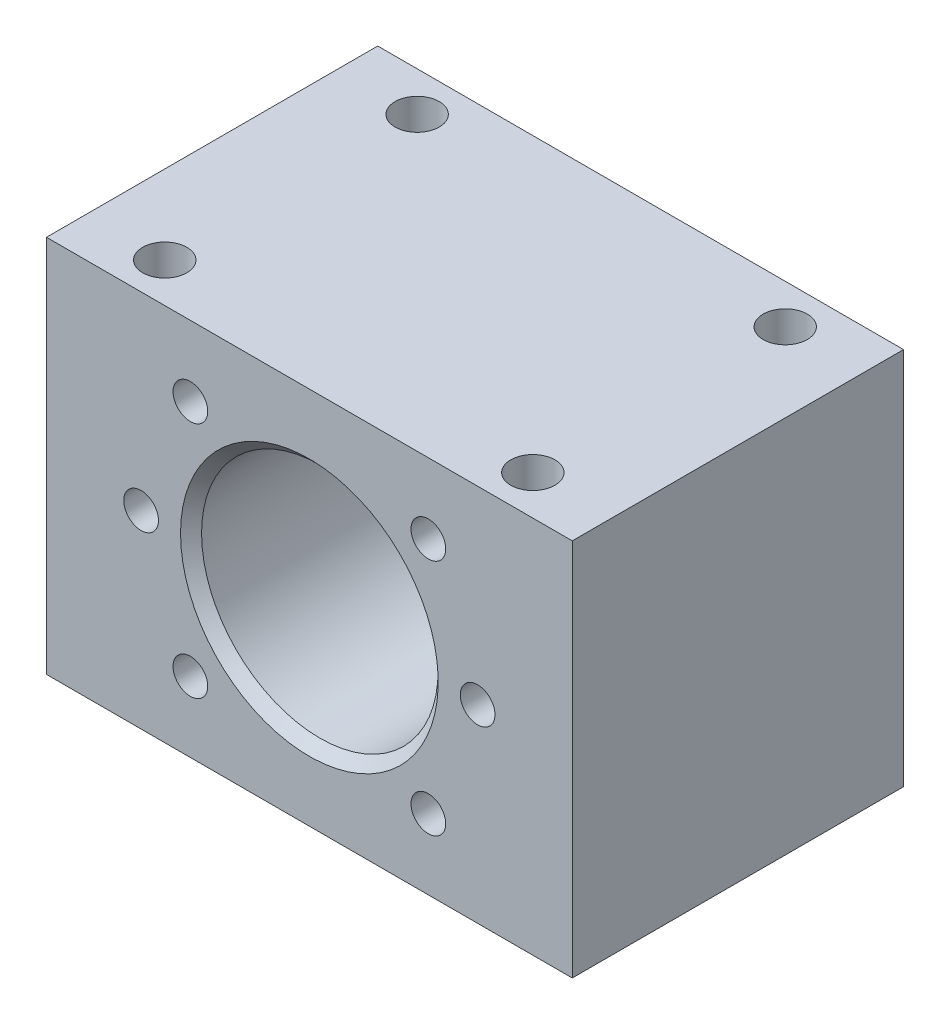
SolidWorks part; units mm, degrees
material "Alliage 1060"
ref_plane "Plan de face" through (0, 0, 0) normal (0, 0, 1) x (1, 0, 0)
ref_plane "Plan de dessus" through (0, 0, 0) normal (0, 1, 0) x (1, 0, 0)
ref_plane "Plan de droite" through (0, 0, 0) normal (1, 0, 0) x (0, 0, -1)
sketch "Esquisse1" plane through (0, 0, 0) normal (0, 0, 1) x (1, 0, 0)
  line L1 (-25, -18) -> (25, -18)
  line L2 (-25, -18) -> (-25, 18)
  line L3 (-25, 18) -> (25, 18)
  line L4 (25, -18) -> (25, 18)
  line L5 (-25, -18) -> (25, 18) construction
  line L6 (-25, 18) -> (25, -18) construction
  point P0 (0, 0)
  dimension "D1" = 36
  dimension "D2" = 50
extrude "Boss.-Extru.1" add sketch "Esquisse1" along normal blind 31.5
sketch "Esquisse2" plane through (0, 0, 31.5) normal (0, 0, 1) x (1, 0, 0)
  circle A0 centre (0, 0) radius 11.25
  dimension "D1" = 22.5
extrude "Enlèv. mat.-Extru.1" cut sketch "Esquisse2" against normal blind 31.5
sketch "Esquisse3" plane through (0, 0, 31.5) normal (0, 0, 1) x (1, 0, 0)
  line L0 (0, 0) -> (-25, 0) construction
  line L1 (-25, 18) -> (-25, -18) construction
  line L2 (0, 0) -> (-15.8009, 15.8009) construction
  line L3 (0, 0) -> (-15.8009, -15.8009) construction
  line L4 (0, 18) -> (0, -18) construction
  line L5 (25, 18) -> (-25, 18) construction
  line L6 (-25, -18) -> (25, -18) construction
  circle A0 centre (0, 0) radius 16 construction
  circle A2 centre (-11.3137, 11.3137) radius 2.75
  circle A3 centre (-16, 0) radius 2.75
  circle A4 centre (-11.3137, -11.3137) radius 2.75
  circle A5 centre (11.3137, -11.3137) radius 2.75
  circle A6 centre (16, 0) radius 2.75
  circle A7 centre (11.3137, 11.3137) radius 2.75
  dimension "D1" = 32
  dimension "D2" = 45
  dimension "D3" = 5.5
  dimension "D4" = 5.5
  dimension "D5" = 5.5
  dimension "D6" = 16
hole_wizard "Trou taraudé M4x0.71" positions "Esquisse4" profile "Esquisse5" tap size "M4x0.7" standard "Ansi Metric"
sketch "Esquisse4" plane through (0, 0, 31.5) normal (0, 0, 1) x (1, 0, 0)
  point P0 (-11.3137, 11.3137)
  point P4 (-16, 0)
  point P7 (-11.3137, -11.3137)
  point P10 (11.3137, -11.3137)
  point P13 (16, 0)
  point P16 (11.3137, 11.3137)
sketch "Esquisse5" plane through (-11.3137, 11.3137, 31.5) normal (1, 0, 0) x (0, -1, 0)
  line L0 (0, 0) -> (0, 12.9914)
  line L1 (0, 12.9914) -> (1.65, 12)
  line L2 (1.65, 12) -> (1.65, 0)
  line L5 (1.65, 0) -> (0, 0)
  line L10 (0, 12.9914) -> (-1.65, 12) construction
  line L11 (0, -6.35) -> (0, 107.95) construction
  dimension "Diamètre du trou pour taraudage" = 3.3
  dimension "Profondeur du trou pour taraudage" = 12
  dimension "Angle de pointe" = 118
cosmetic thread "Filetage de perçage1" parameters "D1"=8, "D2"=4
cosmetic thread "Filetage de perçage2" parameters "D1"=8, "D2"=4
cosmetic thread "Filetage de perçage3" parameters "D1"=8, "D2"=4
cosmetic thread "Filetage de perçage4" parameters "D1"=8, "D2"=4
cosmetic thread "Filetage de perçage5" parameters "D1"=8, "D2"=4
cosmetic thread "Filetage de perçage6" parameters "D1"=8, "D2"=4
sketch "Esquisse6" plane through (0, 18, 0) normal (0, 1, 0) x (1, 0, 0)
  line L0 (0, 0) -> (0, -31.5) construction
  line L1 (25, 0) -> (-25, 0) construction
  line L2 (25, -31.5) -> (-25, -31.5) construction
  line L3 (-25, -15.75) -> (25, -15.75) construction
  line L4 (-25, -31.5) -> (-25, 0) construction
  line L5 (25, -31.5) -> (25, 0) construction
  circle A0 centre (-17.5, -3.75) radius 2.5 construction
  circle A1 centre (-17.5, -27.75) radius 2.5 construction
  circle A2 centre (17.5, -27.75) radius 2.5 construction
  circle A3 centre (17.5, -3.75) radius 2.5 construction
  dimension "D1" = 17.5
  dimension "D2" = 12
  dimension "D3" = 5
hole_wizard "Trou taraudé M5x0.81" positions "Esquisse7" profile "Esquisse8" tap size "M5x0.8" standard "Ansi Metric"
sketch "Esquisse7" plane through (0, 18, 0) normal (0, 1, 0) x (1, 0, 0)
  point P0 (-17.5, -27.75)
  point P3 (-17.5, -3.75)
  point P6 (17.5, -3.75)
  point P9 (17.5, -27.75)
sketch "Esquisse8" plane through (-17.5, 18, 27.75) normal (1, 0, 0) x (0, 0, 1)
  line L0 (0, 0) -> (0, 15.2618)
  line L1 (0, 15.2618) -> (2.1, 14)
  line L2 (2.1, 14) -> (2.1, 0)
  line L5 (2.1, 0) -> (0, 0)
  line L10 (0, 15.2618) -> (-2.1, 14) construction
  line L11 (0, -6.35) -> (0, 107.95) construction
  dimension "Diamètre du trou pour taraudage" = 4.2
  dimension "Profondeur du trou pour taraudage" = 14
  dimension "Angle de pointe" = 118
cosmetic thread "Filetage de perçage7" parameters "D1"=10, "D2"=5
cosmetic thread "Filetage de perçage8" parameters "D1"=10, "D2"=5
cosmetic thread "Filetage de perçage9" parameters "D1"=10, "D2"=5
cosmetic thread "Filetage de perçage10" parameters "D1"=10, "D2"=5
chamfer "Chanfrein1" distance 1 angle 45 2 edges at (11.25, 0, 0) (11.25, 0, 31.5)
